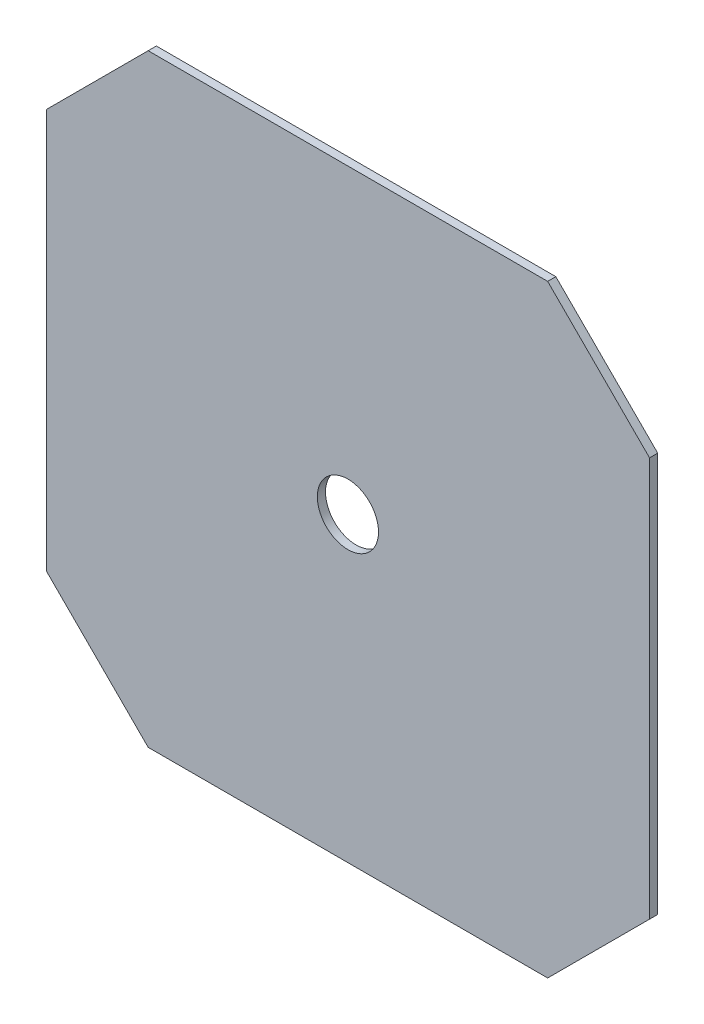
SolidWorks part; units mm, degrees
ref_plane "Front Plane" through (0, 0, 0) normal (0, 0, 1) x (1, 0, 0)
ref_plane "Top Plane" through (0, 0, 0) normal (0, 1, 0) x (1, 0, 0)
ref_plane "Right Plane" through (0, 0, 0) normal (1, 0, 0) x (0, 0, -1)
sketch "Sketch1" plane through (0, 0, 0) normal (0, 0, 1) x (1, 0, 0)
  line L0 (-74, 49) -> (-49, 74)
  line L1 (-49, -74) -> (49, -74)
  line L2 (-74, -49) -> (-74, 49)
  line L3 (-49, 74) -> (49, 74)
  line L4 (74, -49) -> (74, 49)
  line L5 (-74, -74) -> (74, 74) construction
  line L6 (-74, 74) -> (74, -74) construction
  line L7 (49, 74) -> (74, 49)
  line L8 (49, -74) -> (74, -49)
  line L9 (-74, -49) -> (-49, -74)
  point P0 (0, 0)
  dimension "D1" = 148
extrude "Boss-Extrude1" add sketch "Sketch1" along normal blind 2
sketch "Sketch2" plane through (0, 0, 2) normal (0, 0, 1) x (1, 0, 0)
  circle A0 centre (0, 0) radius 7.5
  dimension "D1" = 15
extrude "Cut-Extrude1" cut sketch "Sketch2" against normal blind 10
